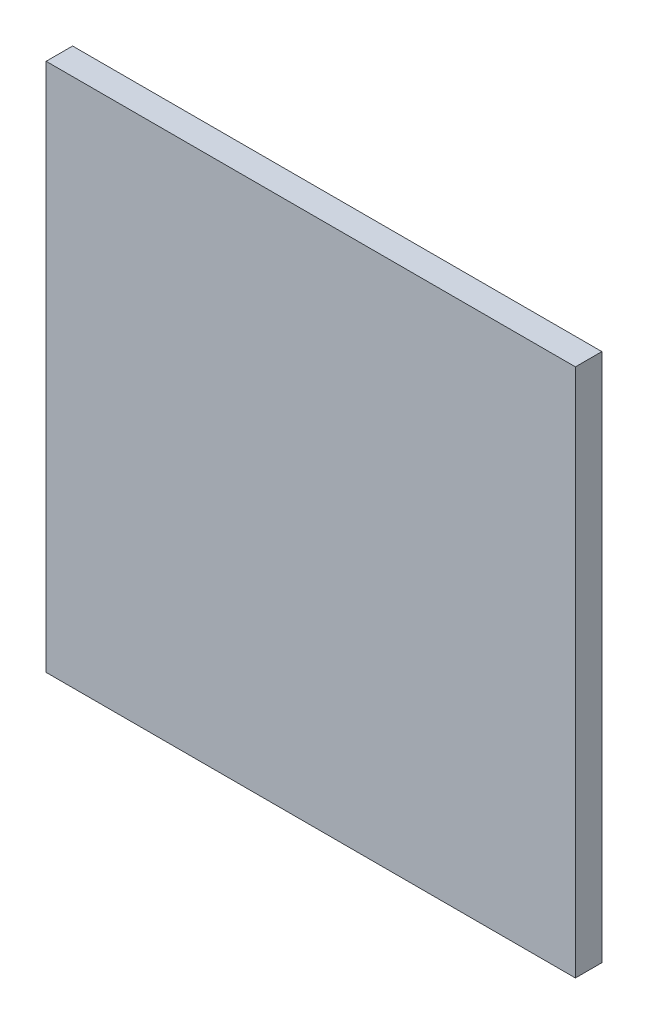
SolidWorks part; units mm, degrees
ref_plane "Plan de face" through (0, 0, 0) normal (0, 0, 1) x (1, 0, 0)
ref_plane "Plan de dessus" through (0, 0, 0) normal (0, 1, 0) x (1, 0, 0)
ref_plane "Plan de droite" through (0, 0, 0) normal (1, 0, 0) x (0, 0, -1)
sketch "Esquisse1" plane through (0, 0, 0) normal (0, 0, 1) x (1, 0, 0)
  line L1 (0, 100) -> (100, 100)
  line L2 (0, 100) -> (0, 0)
  line L3 (0, 0) -> (100, 0)
  line L4 (100, 100) -> (100, 0)
  point P4 (0, 0)
  dimension "D1" = 100
  dimension "D2" = 100
extrude "Boss.-Extru.1" add sketch "Esquisse1" along normal blind 5
